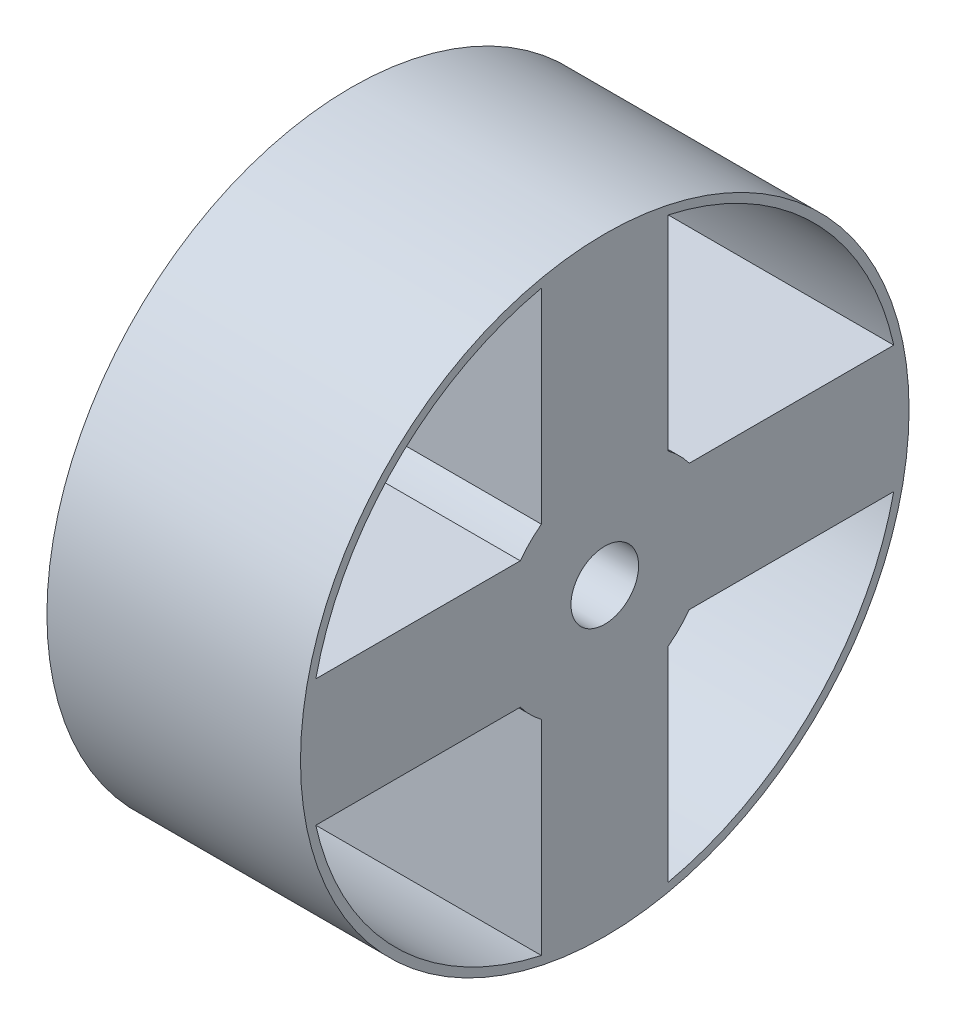
SolidWorks part; units mm, degrees
material "Alloy Steel"
ref_plane "Front Plane" through (0, 0, 0) normal (0, 0, 1) x (1, 0, 0)
ref_plane "Top Plane" through (0, 0, 0) normal (0, 1, 0) x (1, 0, 0)
ref_plane "Right Plane" through (0, 0, 0) normal (1, 0, 0) x (0, 0, -1)
sketch "Sketch1" plane through (0, 0, 0) normal (1, 0, 0) x (0, 0, -1)
  line L0 (0, 99.9086) -> (0, -103.5139) construction
  line L1 (-105.1228, 0) -> (106.8536, 0) construction
  line L2 (-86.8349, 19.05) -> (-25.4, 19.05)
  line L3 (-19.05, 86.8349) -> (-19.05, 25.4)
  line L4 (-86.8349, -19.05) -> (-25.4, -19.05)
  line L5 (19.05, 86.8349) -> (19.05, 25.4)
  line L6 (86.8349, -19.05) -> (25.4, -19.05)
  line L7 (86.8349, 19.05) -> (25.4, 19.05)
  line L8 (19.05, -86.8349) -> (19.05, -25.4)
  line L9 (-19.05, -86.8349) -> (-19.05, -25.4)
  arc A0 (19.05, 86.8349) -> (-19.05, 86.8349) centre (0, 0) ccw
  arc A1 (-25.4, -19.05) -> (-19.05, -25.4) centre (0, 0) ccw
  arc A2 (19.05, -25.4) -> (25.4, -19.05) centre (0, 0) ccw
  arc A3 (25.4, 19.05) -> (19.05, 25.4) centre (0, 0) ccw
  arc A4 (-19.05, 25.4) -> (-25.4, 19.05) centre (0, 0) ccw
  arc A5 (-86.8349, 19.05) -> (-86.8349, -19.05) centre (0, 0) ccw
  arc A6 (-19.05, -86.8349) -> (19.05, -86.8349) centre (0, 0) ccw
  arc A7 (86.8349, -19.05) -> (86.8349, 19.05) centre (0, 0) ccw
  dimension "D1" = 177.8
  dimension "D2" = 63.5
  dimension "D3" = 19.05
  dimension "D4" = 19.05
extrude "Boss-Extrude1" add sketch "Sketch1" along normal blind 76.2
sketch "Sketch2" plane through (76.2, 0, 0) normal (1, 0, 0) x (0, 0, -1)
  circle A0 centre (0, 0) radius 88.9
  circle A1 centre (0, 0) radius 91.44
  dimension "D1" = 182.88
extrude "Boss-Extrude2" add sketch "Sketch2" against normal blind 76.2
sketch "Sketch3" plane through (76.2, 0, 0) normal (1, 0, 0) x (0, 0, -1)
  circle A0 centre (0, 0) radius 10.16
  dimension "D1" = 20.32
extrude "Cut-Extrude1" cut sketch "Sketch3" against normal blind 88.9
